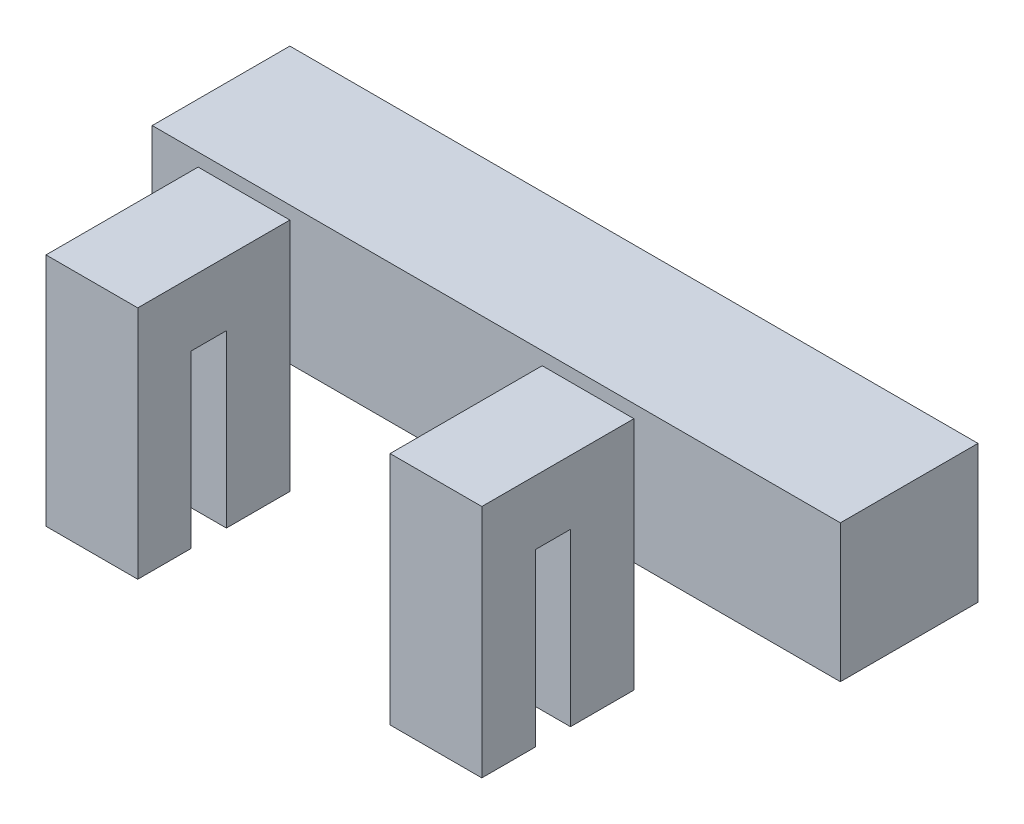
SolidWorks part; units mm, degrees
ref_plane "Front" through (0, 0, 0) normal (0, 0, 1) x (1, 0, 0)
ref_plane "Top" through (0, 0, 0) normal (0, 1, 0) x (1, 0, 0)
ref_plane "Right" through (0, 0, 0) normal (1, 0, 0) x (0, 0, -1)
sketch "Esquisse1" plane through (0, 0, 0) normal (0, 0, 1) x (1, 0, 0)
  line L1 (0, 0) -> (-150, 0)
  line L2 (0, 0) -> (0, 30)
  line L3 (0, 30) -> (-150, 30)
  line L4 (-150, 0) -> (-150, 30)
  dimension "D1" = 150
  dimension "D2" = 30
extrude "Boss.-Extru.1" add sketch "Esquisse1" along normal blind 30
sketch "Esquisse2" plane through (-150, 0, 0) normal (-1, 0, 0) x (0, 0, 1)
  line L0 (30, 30) -> (30, 0) construction
  line L1 (30, 27.1582) -> (63.1562, 27.1582)
  line L2 (30, 27.1582) -> (30, -24.0798)
  line L3 (30, -24.0798) -> (43.8334, -24.0798)
  line L4 (63.1562, 27.1582) -> (63.1562, -24.0798)
  line L5 (51.5046, -24.0798) -> (63.1562, -24.0798)
  line L7 (43.8334, -24.0798) -> (43.8334, 13.1907)
  line L8 (43.8334, 13.1907) -> (51.5046, 13.1907)
  line L9 (51.5046, -24.0798) -> (51.5046, 13.1907)
extrude "Boss.-Extru.2" add sketch "Esquisse2" against normal blind 20 from offset 10 offset against normal yes
pattern_linear "Répétition linéaire1" count 2 spacing 75 along (1, 0, 0) of "Boss.-Extru.2"
